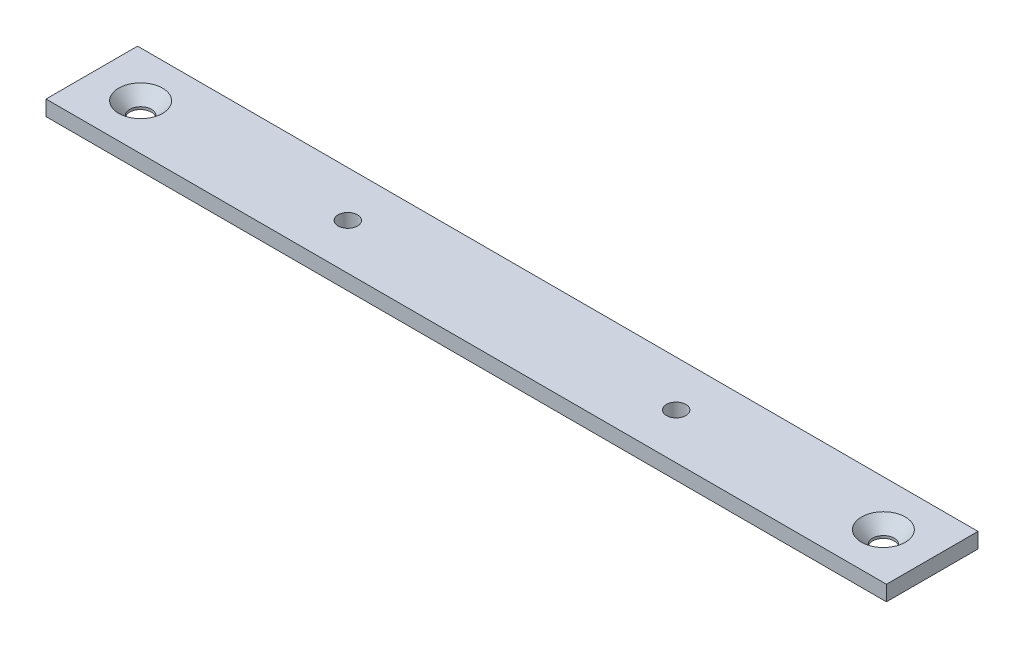
SolidWorks part; units mm, degrees
material "6061-T6 (SS)"
ref_plane "Front Plane" through (0, 0, 0) normal (0, 0, 1) x (1, 0, 0)
ref_plane "Top Plane" through (0, 0, 0) normal (0, 1, 0) x (1, 0, 0)
ref_plane "Right Plane" through (0, 0, 0) normal (1, 0, 0) x (0, 0, -1)
sketch "Sketch1" plane through (0, 0, 0) normal (0, 1, 0) x (1, 0, 0)
  line L1 (-87.4395, -9.525) -> (87.4395, -9.525)
  line L2 (-87.4395, -9.525) -> (-87.4395, 9.525)
  line L3 (-87.4395, 9.525) -> (87.4395, 9.525)
  line L4 (87.4395, -9.525) -> (87.4395, 9.525)
  line L5 (-87.4395, -9.525) -> (87.4395, 9.525) construction
  line L6 (-87.4395, 9.525) -> (87.4395, -9.525) construction
  point P0 (0, 0)
  dimension "D1" = 174.879
  dimension "D2" = 19.05
extrude "Boss-Extrude1" add sketch "Sketch1" along normal blind 3.175
hole_wizard "#10-32 Tapped Hole1" positions "Sketch7" profile "Sketch6" tap size "#10-32" standard "Ansi Inch"
sketch "Sketch7" plane through (0, 3.175, 0) normal (0, 1, 0) x (-1, 0, 0)
  point P0 (34.163, 0)
  point P1 (-34.163, 0)
  dimension "D1" = 68.326
  dimension "D2" = 34.163
sketch "Sketch6" plane through (-34.163, 3.175, 0) normal (1, 0, 0) x (0, 0, 1)
  line L0 (0, 0) -> (0, 13.1513)
  line L1 (0, 13.1513) -> (2.0193, 11.938)
  line L2 (2.0193, 11.938) -> (2.0193, 0)
  line L5 (2.0193, 0) -> (0, 0)
  line L10 (0, 13.1513) -> (-2.0193, 11.938) construction
  line L11 (0, -6.35) -> (0, 107.95) construction
  dimension "Tap Drill Dia." = 4.0386
  dimension "Tap Drill Depth" = 11.938
  dimension "Drill Angle" = 118
hole_wizard "CSK for #8 Flat Head Socket Cap Screw1" positions "Sketch9" profile "Sketch10" countersink size "#8" standard "Ansi Inch" end condition through all
sketch "Sketch9" plane through (0, 3.175, 0) normal (0, 1, 0) x (-1, 0, 0)
  line L0 (-87.4395, -9.525) -> (87.4395, -9.525) construction
  line L1 (-87.4395, 9.525) -> (-87.4395, -9.525) construction
  line L2 (87.4395, -9.525) -> (87.4395, 9.525) construction
  point P0 (77.2795, 0)
  point P1 (-77.2795, 0)
  dimension "D1" = 9.525
  dimension "D2" = 10.16
  dimension "D3" = 10.16
sketch "Sketch10" plane through (-77.2795, 3.175, 0) normal (1, 0, 0) x (0, 0, 1)
  line L0 (0, 0) -> (0, 3.175)
  line L1 (0, 3.175) -> (2.2479, 3.175)
  line L2 (2.2479, 3.175) -> (2.2479, 2.659)
  line L3 (2.2479, 2.659) -> (4.5593, 0)
  line L5 (4.5593, 0) -> (0, 0)
  line L6 (-2.2479, 2.659) -> (-4.5593, 0) construction
  line L11 (0, -6.35) -> (0, 107.95) construction
  dimension "Thru Hole Dia." = 4.4958
  dimension "Thru Hole Depth" = 3.175
  dimension "Near C'Sink Dia." = 9.1186
  dimension "Near C'Sink Angle" = 82
